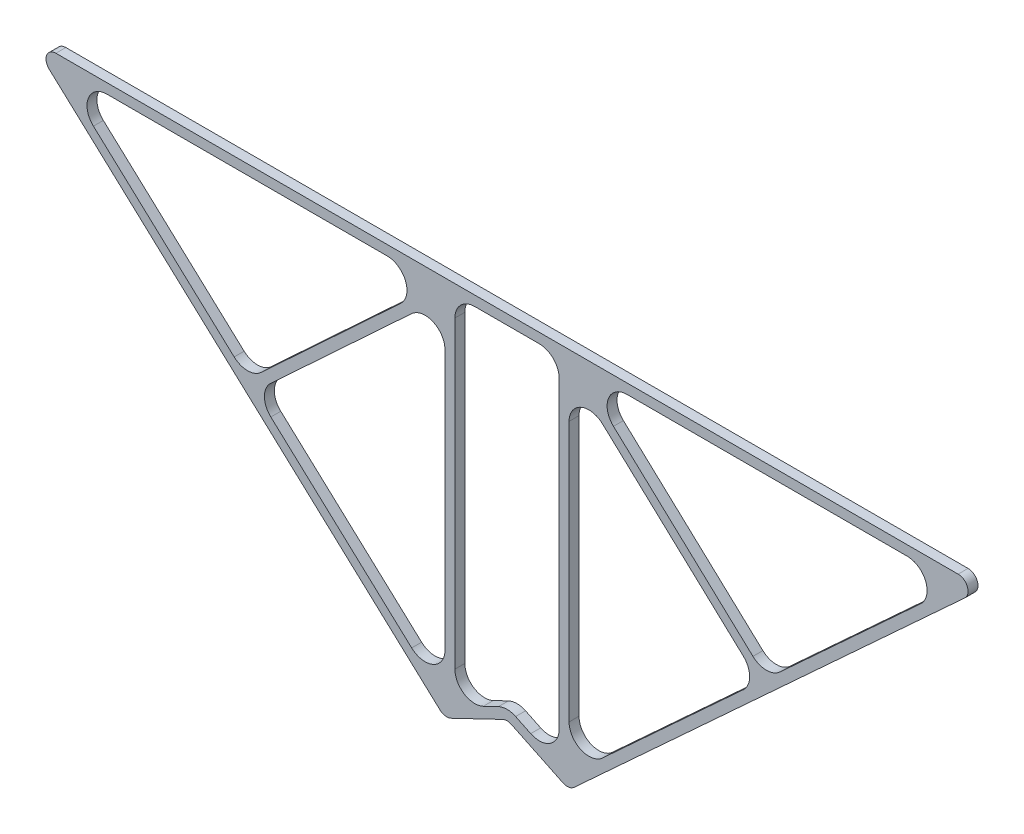
SolidWorks part; units mm, degrees
ref_plane "Front Plane" through (0, 0, 0) normal (0, 0, 1) x (1, 0, 0)
ref_plane "Top Plane" through (0, 0, 0) normal (0, 1, 0) x (1, 0, 0)
ref_plane "Right Plane" through (0, 0, 0) normal (1, 0, 0) x (0, 0, -1)
sketch "Sketch1" plane through (0, 0, 0) normal (0, 0, 1) x (1, 0, 0)
  line L0 (-19.8438, 0) -> (19.8438, 0) construction
  line L1 (-19.8438, 0) -> (0, 9.525)
  line L2 (0, 9.525) -> (19.8438, 0)
  line L3 (-19.8438, 0) -> (-152.4, 121.92)
  line L4 (-152.4, 121.92) -> (152.4, 121.92)
  line L5 (152.4, 121.92) -> (19.8438, 0)
  point P4 (0, 0)
  dimension "D1" = 39.6875
  dimension "D2" = 9.525
  dimension "D3" = 180.099
  dimension "D4" = 304.8
  dimension "D5" = 121.92
extrude "Boss-Extrude1" add sketch "Sketch1" along normal blind 3.175
fillet "Fillet1" radius 3.175 5 edges at (0, 9.525, 1.5875) (-19.8438, 0, 1.5875) (-152.4, 121.92, 1.5875) (19.8438, 0, 1.5875) (152.4, 121.92, 1.5875)
sketch "Sketch2" plane through (0, 0, 3.175) normal (0, 0, 1) x (1, 0, 0)
  line L0 (144.2579, 118.745) -> (-144.2579, 118.745)
  line L1 (-144.2579, 118.745) -> (-19.278, 3.7934)
  line L2 (-19.278, 3.7934) -> (-2.7478, 11.7279)
  line L3 (2.7478, 11.7279) -> (19.278, 3.7934)
  line L4 (19.278, 3.7934) -> (144.2579, 118.745)
  line L5 (-146.4073, 116.4081) -> (-21.4273, 1.4565)
  line L6 (-17.9041, 0.931) -> (-1.3739, 8.8655)
  line L7 (1.3739, 8.8655) -> (17.9041, 0.931)
  line L8 (21.4273, 1.4565) -> (146.4073, 116.4081)
  line L9 (144.2579, 121.92) -> (-144.2579, 121.92)
  line L10 (-146.4073, 116.4081) -> (-21.4273, 1.4565)
  line L11 (-17.9041, 0.931) -> (-1.3739, 8.8655)
  line L12 (1.3739, 8.8655) -> (17.9041, 0.931)
  line L13 (21.4273, 1.4565) -> (146.4073, 116.4081)
  line L14 (144.2579, 121.92) -> (-144.2579, 121.92)
  line L15 (-19.8438, 118.745) -> (-19.8438, 4.3137)
  line L16 (19.8437, 118.745) -> (19.8438, 4.3137)
  line L17 (-16.6688, 118.745) -> (-16.6687, 4.3137)
  line L18 (16.6687, 118.745) -> (16.6687, 4.3137)
  line L19 (-19.8438, 118.745) -> (-81.768, 61.2692)
  line L20 (19.8437, 118.745) -> (81.768, 61.2692)
  line L23 (-20.9237, 119.9085) -> (-82.94, 62.3472)
  line L24 (-18.7638, 117.5815) -> (-82.9303, 58.0245)
  line L25 (18.7638, 117.5815) -> (82.9303, 58.0245)
  line L26 (20.9237, 119.9085) -> (82.94, 62.3472)
  line L27 (-18.7638, 117.5815) -> (-80.688, 60.1056) construction
  line L28 (-20.9237, 119.9085) -> (-82.8479, 62.4327) construction
  line L29 (20.9237, 119.9085) -> (82.8479, 62.4327) construction
  line L30 (18.7638, 117.5815) -> (80.688, 60.1056) construction
  arc A0 (-144.2579, 118.745) -> (-144.2579, 118.745) centre (-144.2579, 118.745) ccw
  arc A1 (-19.278, 3.7934) -> (-19.278, 3.7934) centre (-19.278, 3.7934) ccw
  arc A2 (2.7478, 11.7279) -> (-2.7478, 11.7279) centre (0, 6.0032) ccw
  arc A3 (19.278, 3.7934) -> (19.278, 3.7934) centre (19.278, 3.7934) ccw
  arc A4 (144.2579, 118.745) -> (144.2579, 118.745) centre (144.2579, 118.745) ccw
  arc A5 (-21.4273, 1.4565) -> (-17.9041, 0.931) centre (-19.278, 3.7934) ccw
  arc A6 (1.3739, 8.8655) -> (-1.3739, 8.8655) centre (0, 6.0032) ccw
  arc A7 (17.9041, 0.931) -> (21.4273, 1.4565) centre (19.278, 3.7934) ccw
  arc A8 (146.4073, 116.4081) -> (144.2579, 121.92) centre (144.2579, 118.745) ccw
  arc A9 (-144.2579, 121.92) -> (-146.4073, 116.4081) centre (-144.2579, 118.745) ccw
  arc A10 (-21.4273, 1.4565) -> (-17.9041, 0.931) centre (-19.278, 3.7934) ccw
  arc A11 (1.3739, 8.8655) -> (-1.3739, 8.8655) centre (0, 6.0032) ccw
  arc A12 (17.9041, 0.931) -> (21.4273, 1.4565) centre (19.278, 3.7934) ccw
  arc A13 (146.4073, 116.4081) -> (144.2579, 121.92) centre (144.2579, 118.745) ccw
  arc A14 (-144.2579, 121.92) -> (-146.4073, 116.4081) centre (-144.2579, 118.745) ccw
  dimension "D3" = 19.8438
  dimension "D4" = 39.6875
  dimension "D1" = 0
  dimension "D2" = 3.175
  dimension "D5" = 3.175
  dimension "D6" = 3.175
  dimension "D7" = 1.5875
  dimension "D8" = 1.5875
  dimension "D9" = 1.5875
  dimension "D10" = 1.5875
extrude "Cut-Extrude1" cut sketch "Sketch2" against normal through all both and the other way through all contours L23 L0 L1 | L15 L24 L1 | A2 L3 L18 L0 L17 L2 | L25 L16 L4 | L0 L26 L4
fillet "Fillet2" radius 6.35 16 edges at (19.8438, 4.3137, 1.5875) (19.8437, 116.5791, 1.5875) (80.5959, 60.1912, 1.5875) (-16.6687, 5.0458, 1.5875) (-16.6688, 118.745, 1.5875) (16.6687, 118.745, 1.5875) (16.6687, 5.0458, 1.5875) (-19.8438, 116.5791, 1.5875) (-19.8438, 4.3137, 1.5875) (-144.2579, 118.745, 1.5875) (-22.1773, 118.745, 1.5875) (-82.94, 62.3472, 1.5875) (144.2579, 118.745, 1.5875) (82.94, 62.3472, 1.5875) (22.1773, 118.745, 1.5875) (-80.5959, 60.1912, 1.5875)
